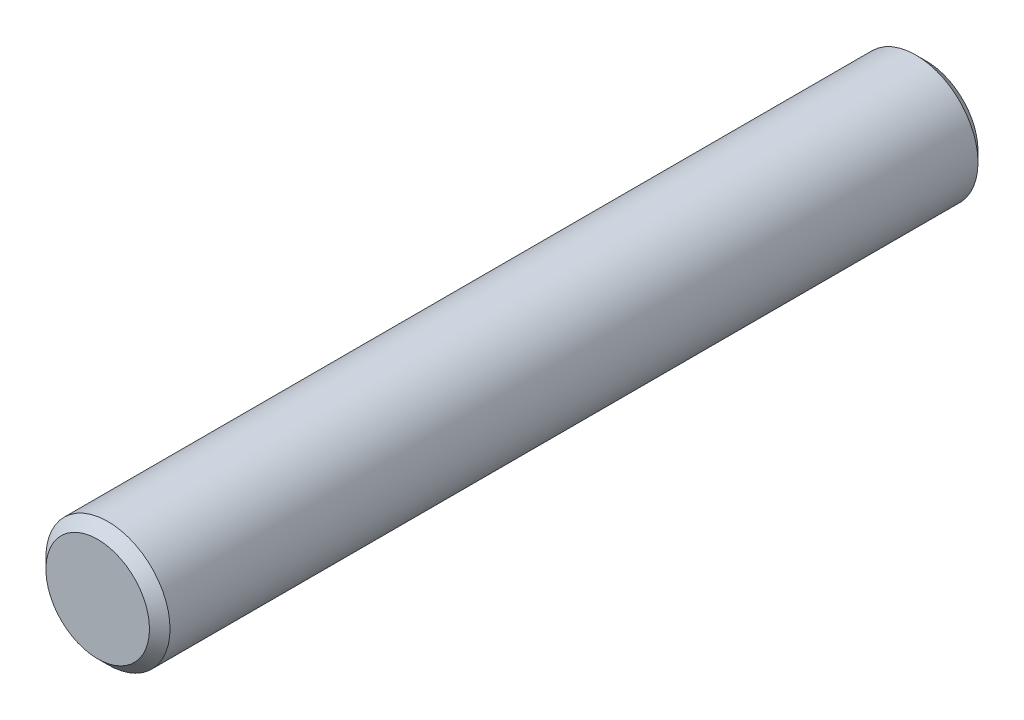
SolidWorks part; units mm, degrees
ref_plane "Front Plane" through (0, 0, 0) normal (0, 0, 1) x (1, 0, 0)
ref_plane "Top Plane" through (0, 0, 0) normal (0, 1, 0) x (1, 0, 0)
ref_plane "Right Plane" through (0, 0, 0) normal (1, 0, 0) x (0, 0, -1)
sketch "Sketch1" plane through (0, 0, 0) normal (0, 0, 1) x (1, 0, 0)
  circle A0 centre (0, 0) radius 0.3745
  dimension "D1" = 0.749
extrude "Boss-Extrude1" add sketch "Sketch1" along normal mid plane 5
chamfer "Chamfer1" distance 0.062 angle 45 2 edges at (0.3745, 0, -2.5) (0.3745, 0, 2.5)
